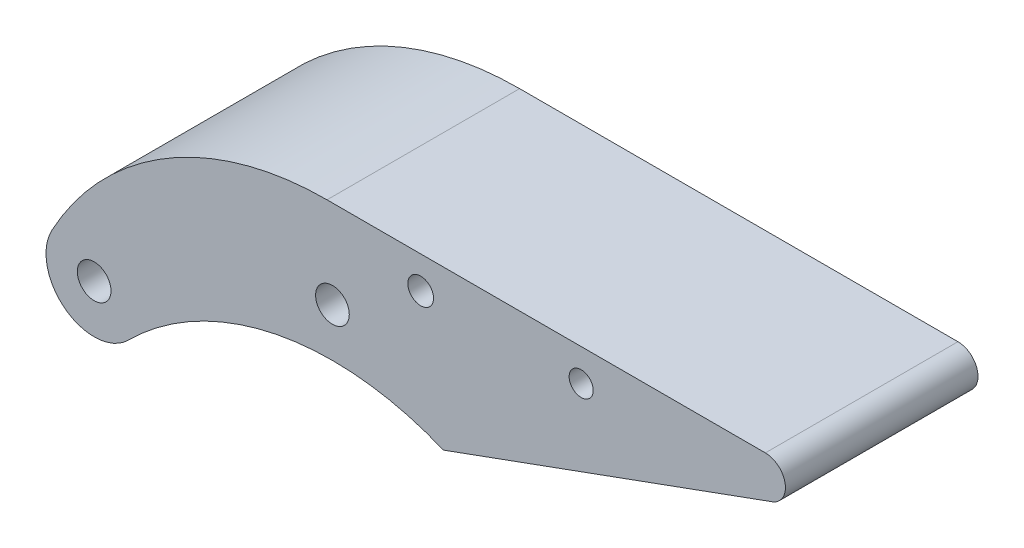
SolidWorks part; units mm, degrees
material "ABS"
ref_plane "前视基准面" through (0, 0, 0) normal (0, 0, 1) x (1, 0, 0)
ref_plane "上视基准面" through (0, 0, 0) normal (0, 1, 0) x (1, 0, 0)
ref_plane "右视基准面" through (0, 0, 0) normal (1, 0, 0) x (0, 0, -1)
other "Configuration Table"
sketch "草图1" plane through (0, 0, 0) normal (0, 0, 1) x (1, 0, 0)
  line L0 (0, 42) -> (0, 0) construction
  line L1 (0, 0) -> (-29.6985, 29.6985) construction
  line L2 (-29.6985, 53) -> (68.1355, 53)
  line L3 (-9.0635, 24.9019) -> (68.1355, 53)
  line L4 (0, 0) -> (13.8339, 33.2359) construction
  line L5 (0, 0) -> (-9.0635, 24.9019) construction
  circle A0 centre (0, 0) radius 42 construction
  circle A1 centre (0, 42) radius 2.1
  circle A2 centre (-29.6985, 29.6985) radius 2.1
  circle A3 centre (-29.6985, 29.6985) radius 6
  circle A4 centre (0, 0) radius 36
  circle A7 centre (-0.6716, 14) radius 39
  circle A8 centre (0, 0) radius 26.5 construction
  dimension "D1" = 84
  dimension "D2" = 4.2
  dimension "D3" = 45
  dimension "D4" = 72
  dimension "D6" = 78
  dimension "D9" = 53
  dimension "D5" = 53
  dimension "D7" = 20
extrude "凸台-拉伸1" add sketch "草图1" along normal blind 24
fillet "圆角1" radius 2.5 1 edges at (68.1355, 53, 12)
sketch "草图3" plane through (0, 0, 24) normal (0, 0, 1) x (1, 0, 0)
  line L0 (-0.6716, 53) -> (53.9573, 53) construction
  circle A0 centre (11, 49) radius 1.6
  circle A1 centre (31, 49) radius 1.5
  circle A3 centre (0, 42) radius 2.1 construction
  circle A4 centre (0, 42) radius 2.1
  dimension "D2" = 3.2
  dimension "D3" = 3
  dimension "D5" = 11
  dimension "D1" = 20
  dimension "D4" = 4
extrude "切除-拉伸2" cut sketch "草图3" against normal up to next (24 mm away)
sketch "草图4" plane through (0, 0, 24) normal (0, 0, 1) x (1, 0, 0)
  line L0 (13.8339, 33.2359) -> (54.8123, 48.1508) construction
  line L1 (13.8339, 33.2359) -> (54.8123, 48.1508)
  circle A0 centre (23.8339, 36.8756) radius 1
  dimension "D1" = 2
  dimension "D2" = 10
extrude "切除-拉伸3" [suppressed] cut sketch "草图4" against normal up to next contours A0
